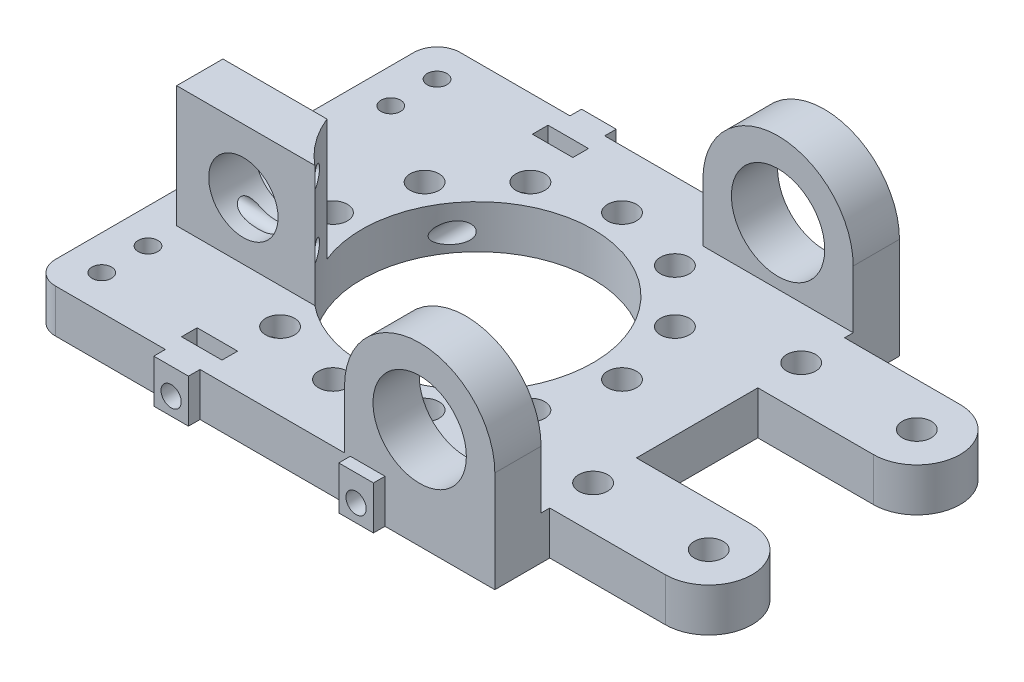
SolidWorks part; units mm, degrees
ref_plane "Front Plane" through (0, 0, 0) normal (0, 0, 1) x (1, 0, 0)
ref_plane "Top Plane" through (0, 0, 0) normal (0, 1, 0) x (1, 0, 0)
ref_plane "Right Plane" through (0, 0, 0) normal (1, 0, 0) x (0, 0, -1)
sketch "Sketch1" plane through (0, 0, 0) normal (0, 1, 0) x (1, 0, 0)
  line L0 (-62.4163, 0) -> (61.9965, 0) construction
  line L1 (-40, 35) -> (40, 35)
  line L2 (-40, 35) -> (-40, -35)
  line L3 (-40, -35) -> (40, -35)
  line L4 (40, 35) -> (40, -35) construction
  line L5 (-40, 35) -> (40, -35) construction
  line L6 (-40, -35) -> (40, 35) construction
  line L7 (40, 35) -> (40, 25.5)
  line L8 (40, 25.5) -> (60, 25.5)
  line L9 (60, 10.5) -> (40, 10.5)
  line L10 (40, 10.5) -> (40, -10.5)
  line L11 (60, -10.5) -> (40, -10.5)
  line L12 (40, -25.5) -> (60, -25.5)
  line L13 (40, -35) -> (40, -25.5)
  arc A0 (60, 25.5) -> (60, 10.5) centre (60, 18) cw
  arc A1 (60, -25.5) -> (60, -10.5) centre (60, -18) ccw
  point P0 (0, 0)
  point P15 (40, 0)
  dimension "D1" = 80
  dimension "D2" = 70
  dimension "D3" = 80
  dimension "D4" = 15
  dimension "D5" = 20
  dimension "D6" = 9.5
extrude "Boss-Extrude1" add sketch "Sketch1" along normal blind 7.5
sketch "Sketch2" plane through (0, 0, 35) normal (0, 0, 1) x (1, 0, 0)
  line L0 (-40, 7.5) -> (40, 7.5) construction
  line L1 (-17, 7.5) -> (-11, 7.5)
  line L2 (-17, 7.5) -> (-17, 0)
  line L3 (-17, 0) -> (-11, 0)
  line L4 (-11, 7.5) -> (-11, 0)
  line L5 (-17, 7.5) -> (-11, 0) construction
  line L6 (-17, 0) -> (-11, 7.5) construction
  line L7 (15, 7.5) -> (21, 7.5)
  line L8 (15, 7.5) -> (15, 0)
  line L9 (15, 0) -> (21, 0)
  line L10 (21, 7.5) -> (21, 0)
  line L11 (15, 7.5) -> (21, 0) construction
  line L12 (15, 0) -> (21, 7.5) construction
  line L13 (-40, 0) -> (40, 0) construction
  line L15 (-40, 7.5) -> (-40, 0) construction
  point P0 (-14, 3.75)
  point P5 (18, 3.75)
  dimension "D1" = 26
  dimension "D2" = 32
  dimension "D3" = 6
extrude "Boss-Extrude2" add sketch "Sketch2" along normal blind 2
sketch "Sketch3" plane through (0, 0, 35) normal (0, 0, 1) x (1, 0, 0)
  line L0 (40, 7.5) -> (40, 0) construction
  line L1 (40, 7.5) -> (14, 7.5)
  line L2 (40, 7.5) -> (40, 17.5)
  line L3 (40, 17.5) -> (14, 17.5) construction
  line L4 (14, 7.5) -> (14, 17.5)
  line L5 (21, 7.5) -> (40, 7.5) construction
  line L6 (21, 0) -> (40, 0) construction
  circle A0 centre (27, 17.5) radius 8.075
  arc A1 (14, 17.5) -> (40, 17.5) centre (27, 17.5) cw
  point P10 (27, 17.5)
  dimension "D3" = 16.15
  dimension "D1" = 26
  dimension "D2" = 17.5
extrude "Boss-Extrude3" add sketch "Sketch3" against normal blind 8
sketch "Sketch4" plane through (0, 0, 0) normal (0, -1, 0) x (1, 0, 0)
  line L0 (-17, 37) -> (-11, 37) construction
  line L1 (-17.5, 29) -> (-10.5, 29)
  line L2 (-17.5, 29) -> (-17.5, 31.7)
  line L3 (-17.5, 31.7) -> (-10.5, 31.7)
  line L4 (-10.5, 29) -> (-10.5, 31.7)
  line L5 (-17.5, 29) -> (-10.5, 31.7) construction
  line L6 (-17.5, 31.7) -> (-10.5, 29) construction
  line L7 (14.5, 29) -> (21.5, 29)
  line L8 (14.5, 29) -> (14.5, 31.7)
  line L9 (14.5, 31.7) -> (21.5, 31.7)
  line L10 (21.5, 29) -> (21.5, 31.7)
  line L11 (14.5, 29) -> (21.5, 31.7) construction
  line L12 (14.5, 31.7) -> (21.5, 29) construction
  line L13 (15, 37) -> (21, 37) construction
  line L14 (-11, 35) -> (15, 35) construction
  point P0 (-14, 30.35)
  point P5 (18, 30.35)
  point P12 (-14, 37)
  point P15 (18, 37)
  dimension "D1" = 7
  dimension "D2" = 2.7
  dimension "D3" = 6
extrude "Cut-Extrude1" cut sketch "Sketch4" against normal up to surface (7.5 mm away) up to face at (17.25, 7.5, 36.5)
sketch "Sketch5" plane through (0, 0, 0) normal (0, -1, 0) x (1, 0, 0)
  line L0 (-40, 0) -> (40, 0) construction
  line L1 (-40, -35) -> (-40, 35) construction
  line L2 (40, 10.5) -> (40, -10.5) construction
  circle A0 centre (-34, 29) radius 1.7
  circle A1 centre (-34, 21) radius 1.7
  dimension "D1" = 3.4
  dimension "D2" = 8
  dimension "D3" = 21
  dimension "D4" = 6
extrude "Cut-Extrude2" cut sketch "Sketch5" against normal through all
mirror "Mirror1" about plane through (0, 0, 0) normal (0, 0, 1) of "Cut-Extrude2", "Cut-Extrude1", "Boss-Extrude3", "Boss-Extrude2"
sketch "Sketch6" plane through (0, 0, 0) normal (0, -1, 0) x (1, 0, 0)
  line L0 (-11, 35) -> (15, 35) construction
  circle A0 centre (2, 0) radius 20
  point P5 (2, 35)
  dimension "D1" = 40
extrude "Cut-Extrude3" cut sketch "Sketch6" against normal through all
sketch "Sketch7" plane through (0, 0, 0) normal (0, -1, 0) x (1, 0, 0)
  line L0 (2, 25) -> (2, -25) construction
  line L1 (-23, 0) -> (27, 0) construction
  circle A0 centre (-23, 0) radius 2.5
  circle A1 centre (2, 0) radius 20 construction
  circle A3 centre (-10.5, 21.6506) radius 2.5
  circle A4 centre (2, 25) radius 2.5
  circle A5 centre (14.5, 21.6506) radius 2.5
  circle A6 centre (23.6506, 12.5) radius 2.5
  circle A7 centre (27, 0) radius 2.5
  circle A8 centre (23.6506, -12.5) radius 2.5
  circle A9 centre (14.5, -21.6506) radius 2.5
  circle A10 centre (2, -25) radius 2.5
  circle A11 centre (-10.5, -21.6506) radius 2.5
  circle A12 centre (-19.6506, -12.5) radius 2.5
  circle A13 centre (-19.6506, 12.5) radius 2.5 [skipped]
  point P2 (2, 0)
  dimension "D2" = 5
  dimension "D1" = 25
  dimension "D3" = 12
extrude "Cut-Extrude4" cut sketch "Sketch7" against normal through all
sketch "Sketch8" plane through (0, 0, -37) normal (0, 0, -1) x (-1, 0, 0)
  line L0 (-15, 7.5) -> (-21, 7.5) construction
  line L1 (11, 7.5) -> (17, 7.5) construction
  circle A0 centre (-18, 3) radius 1.75
  circle A1 centre (14, 3) radius 1.75
  point P4 (-18, 4.75)
  point P7 (-18, 7.5)
  point P10 (14, 7.5)
  dimension "D2" = 3.5
  dimension "D1" = 2.75
extrude "Cut-Extrude5" cut sketch "Sketch8" against normal through all
sketch "Sketch10" plane through (0, 0, 0) normal (0, -1, 0) x (1, 0, 0)
  line L0 (-16.5405, 15.5) -> (-10.6392, 15.5)
  line L1 (-34.5405, 7.5) -> (-16.5405, 7.5)
  line L2 (-34.5405, 7.5) -> (-34.5405, 15.5)
  line L3 (-34.5405, 15.5) -> (-16.5405, 15.5)
  line L4 (-16.5405, 7.5) -> (-16.5405, 15.5) construction
  line L5 (-40, 35) -> (-17, 35) construction
  circle A0 centre (2, 0) radius 20 construction
  arc A1 (-16.5405, 7.5) -> (-10.6392, 15.5) centre (2, 0) cw
  dimension "D1" = 8
  dimension "D2" = 18
  dimension "D3" = 19.5
extrude "Boss-Extrude4" add sketch "Sketch10" against normal offset from surface (28.5 mm away) 21 up to face at (2, 7.5, -22.5) offset beyond the face yes
sketch "Sketch11" plane through (0, 0, 15.5) normal (0, 0, 1) x (1, 0, 0)
  circle A0 centre (-23, 17.5) radius 6
  point P2 (27, 17.5)
  dimension "D1" = 12
  dimension "D2" = 50
extrude "Cut-Extrude6" cut sketch "Sketch11" against normal up to next
sketch "Sketch12" plane through (-34.5405, 0, 0) normal (-1, 0, 0) x (0, 0, 1)
  line L0 (7.5, 17.5) -> (15.5, 17.5) construction
  line L1 (7.5, 28.5) -> (7.5, 7.5) construction
  line L2 (15.5, 28.5) -> (15.5, 7.5) construction
  line L3 (7.5, 23.5) -> (7.5, 11.5) construction
  circle A0 centre (11.5, 23.05) radius 1.5
  circle A1 centre (11.5, 11.95) radius 1.5
  point P12 (11.5, 21.55)
  point P13 (11.5, 13.45)
  point P14 (11.5, 17.5)
  dimension "D2" = 3
  dimension "D1" = 8.1
extrude "Cut-Extrude7" cut sketch "Sketch12" against normal up to next
sketch "Sketch14" plane through (0, 0, 0) normal (0, -1, 0) x (1, 0, 0)
  line L0 (0, 0) -> (89.7656, 0) construction
  line L1 (50, -10.5) -> (50, -25.5) construction
  line L2 (40, -10.5) -> (60, -10.5) construction
  line L3 (60, -25.5) -> (40, -25.5) construction
  circle A0 centre (60, -18) radius 2.5
  circle A1 centre (40, -18) radius 2.5
  circle A2 centre (60, 18) radius 2.5
  circle A3 centre (40, 18) radius 2.5
  dimension "D1" = 5
extrude "Cut-Extrude8" cut sketch "Sketch14" against normal through all
fillet "Fillet1" radius 4 2 edges at (-40, 3.75, -35) (-40, 3.75, 35)
fillet "Fillet2" [suppressed] radius 1.5
